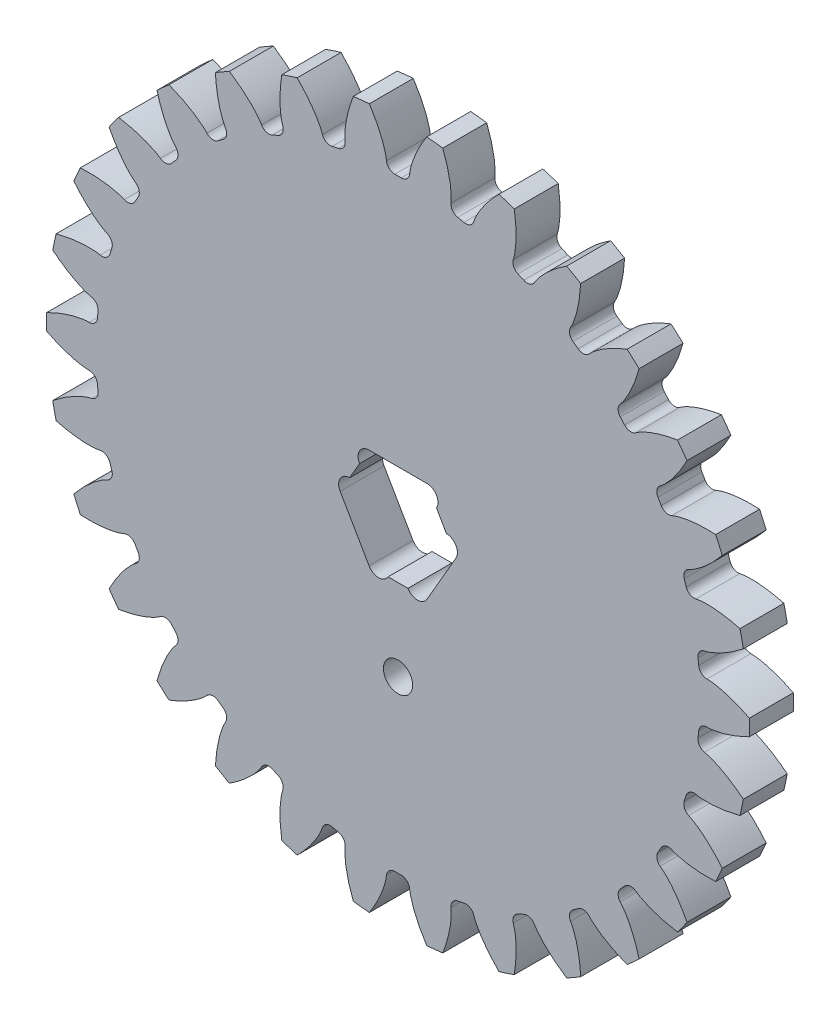
SolidWorks part; units mm, degrees
material "Hexcel AS4C (3000 丝)"
ref_plane "前视基准面" through (0, 0, 0) normal (0, 0, 1) x (1, 0, 0)
ref_plane "上视基准面" through (0, 0, 0) normal (0, 1, 0) x (1, 0, 0)
ref_plane "右视基准面" through (0, 0, 0) normal (1, 0, 0) x (0, 0, -1)
ref_axis "Axis1" through (0, 0, -88.99) along (0, 0, 1)
sketch "草图1" plane through (0, 0, 0) normal (0, 0, 1) x (1, 0, 0)
  circle A0 centre (0, 0) radius 24
extrude "LaShenA" add sketch "草图1" along normal blind 3
sketch "SketchA" plane through (0, 0, 3) normal (0, 0, 1) x (1, 0, 0)
  line L0 (0, 0) -> (0, 24) construction
  arc A0 (0.2184, 20.6238) -> (-0.2184, 20.6238) centre (0, 0) ccw
  arc A1 (2.5339, 24.7321) -> (-2.5339, 24.7321) centre (0, 0) ccw
  arc A2 (-0.2184, 20.6238) -> (-0.7909, 21.1307) centre (-0.2244, 21.1938) cw
  arc A3 (0.7909, 21.1307) -> (0.2184, 20.6238) centre (0.2244, 21.1938) cw
  circle A4 centre (0, 0) radius 21.1431 construction
  circle A5 centre (0, 0) radius 24 construction
  circle A6 centre (0, 0) radius 20.625 construction
  circle A7 centre (0, 0) radius 22.5 construction
  spline S0 degree 3 poles (0.7909, 21.1307) (0.7927, 21.1471) (0.7998, 21.2085) (0.8112, 21.291) (0.8279, 21.3808) (0.8427, 21.4528) (0.8612, 21.5338) (0.8836, 21.6234) (0.9104, 21.7217) (0.9419, 21.8284) (0.9785, 21.9433) (1.0206, 22.0664) (1.0685, 22.1974) (1.1226, 22.3362) (1.1831, 22.4824) (1.2506, 22.636) (1.3252, 22.7967) (1.4073, 22.9642) (1.4973, 23.1383) (1.5954, 23.3187) (1.702, 23.5052) (1.8173, 23.6975) (1.9417, 23.8953) (2.0754, 24.0982) (2.27, 24.3805) (2.4255, 24.5913) (2.5339, 24.7321) knots 0.114617 0.114617 0.114617 0.114617 0.125462 0.155251 0.169305 0.18542 0.203596 0.223834 0.246133 0.270493 0.296915 0.325398 0.355942 0.388548 0.423215 0.459943 0.498732 0.539583 0.582495 0.627469 0.674504 0.7236 0.774757 0.827976 0.883256 1 1 1 1
  spline S1 degree 3 poles (-0.7909, 21.1307) (-0.7927, 21.1471) (-0.7998, 21.2085) (-0.8112, 21.291) (-0.8279, 21.3808) (-0.8427, 21.4528) (-0.8612, 21.5338) (-0.8836, 21.6234) (-0.9104, 21.7217) (-0.9419, 21.8284) (-0.9785, 21.9433) (-1.0206, 22.0664) (-1.0685, 22.1974) (-1.1226, 22.3362) (-1.1831, 22.4824) (-1.2506, 22.636) (-1.3252, 22.7967) (-1.4073, 22.9642) (-1.4973, 23.1383) (-1.5954, 23.3187) (-1.702, 23.5052) (-1.8173, 23.6975) (-1.9417, 23.8953) (-2.0754, 24.0982) (-2.27, 24.3805) (-2.4255, 24.5913) (-2.5339, 24.7321) knots 0.114617 0.114617 0.114617 0.114617 0.125462 0.155251 0.169305 0.18542 0.203596 0.223834 0.246133 0.270493 0.296915 0.325398 0.355942 0.388548 0.423215 0.459943 0.498732 0.539583 0.582495 0.627469 0.674504 0.7236 0.774757 0.827976 0.883256 1 1 1 1
  dimension "D1" = 0.57
  dimension "Db" = 42.2862
  dimension "Da" = 48
  dimension "Df" = 41.25
  dimension "Dn" = 45
extrude "Cut-ExtrudeA" cut sketch "SketchA" against normal blind 3
pattern_circular "www.KYTool.cn" count 30 over 360 about axis through (0, 0, -88.99) along (0, 0, 1) of "Cut-ExtrudeA"
sketch "草图3" plane through (0, 0, 3) normal (0, 0, 1) x (1, 0, 0)
  line L1 (3.9548, 0) -> (1.9774, 3.425)
  line L2 (1.9774, 3.425) -> (-1.9774, 3.425)
  line L3 (-1.9774, 3.425) -> (-3.9548, 0)
  line L4 (-3.9548, 0) -> (-1.9774, -3.425)
  line L5 (-1.9774, -3.425) -> (1.9774, -3.425)
  line L6 (1.9774, -3.425) -> (3.9548, 0)
  circle A0 centre (0, 0) radius 3.425 construction
  dimension "D1" = 6.85
extrude "切除-拉伸2" cut sketch "草图3" against normal through all
sketch "草图4" plane through (0, 0, 3) normal (0, 0, 1) x (1, 0, 0)
  circle A0 centre (0, -9) radius 1
  dimension "D1" = 2
  dimension "D2" = 9
extrude "切除-拉伸3" cut sketch "草图4" against normal through all
sketch "草图5" plane through (0, 0, 3) normal (0, 0, 1) x (1, 0, 0)
  line L1 (-1000, 0) -> (49000, 0) construction
  circle A0 centre (2.9548, 0) radius 1
  circle A1 centre (1.4774, -2.559) radius 1
  circle A2 centre (-1.4774, -2.559) radius 1
  circle A3 centre (-2.9548, 0) radius 1
  circle A4 centre (-1.4774, 2.559) radius 1
  circle A5 centre (1.4774, 2.559) radius 1
  point P18 (0, 0)
  dimension "D1" = 2
  dimension "D2" = 6
extrude "切除-拉伸4" [suppressed] cut sketch "草图5" against normal through all
sketch "草图6" plane through (0, 0, 3) normal (0, 0, 1) x (1, 0, 0)
  line L0 (3.3053, 0.375) -> (3.9548, 0) construction
  line L1 (1.9774, -3.425) -> (3.9548, 0) construction
  line L2 (0, -1000) -> (0, 49000) construction
  line L3 (0, 0) -> (-43301.2702, 25000) construction
  line L4 (-1.9774, 3.425) -> (-3.9548, 0) construction
  circle A0 centre (3.3053, 0.375) radius 0.75
  circle A1 centre (-3.3053, 0.375) radius 0.75
  circle A2 centre (-1.9774, 2.675) radius 0.75
  circle A3 centre (1.3279, -3.05) radius 0.75
  circle A4 centre (-1.3279, -3.05) radius 0.75
  circle A5 centre (1.9774, 2.675) radius 0.75
  point P15 (-2.9661, 1.7125)
  dimension "D1" = 1.5
extrude "切除-拉伸5" cut sketch "草图6" against normal through all
